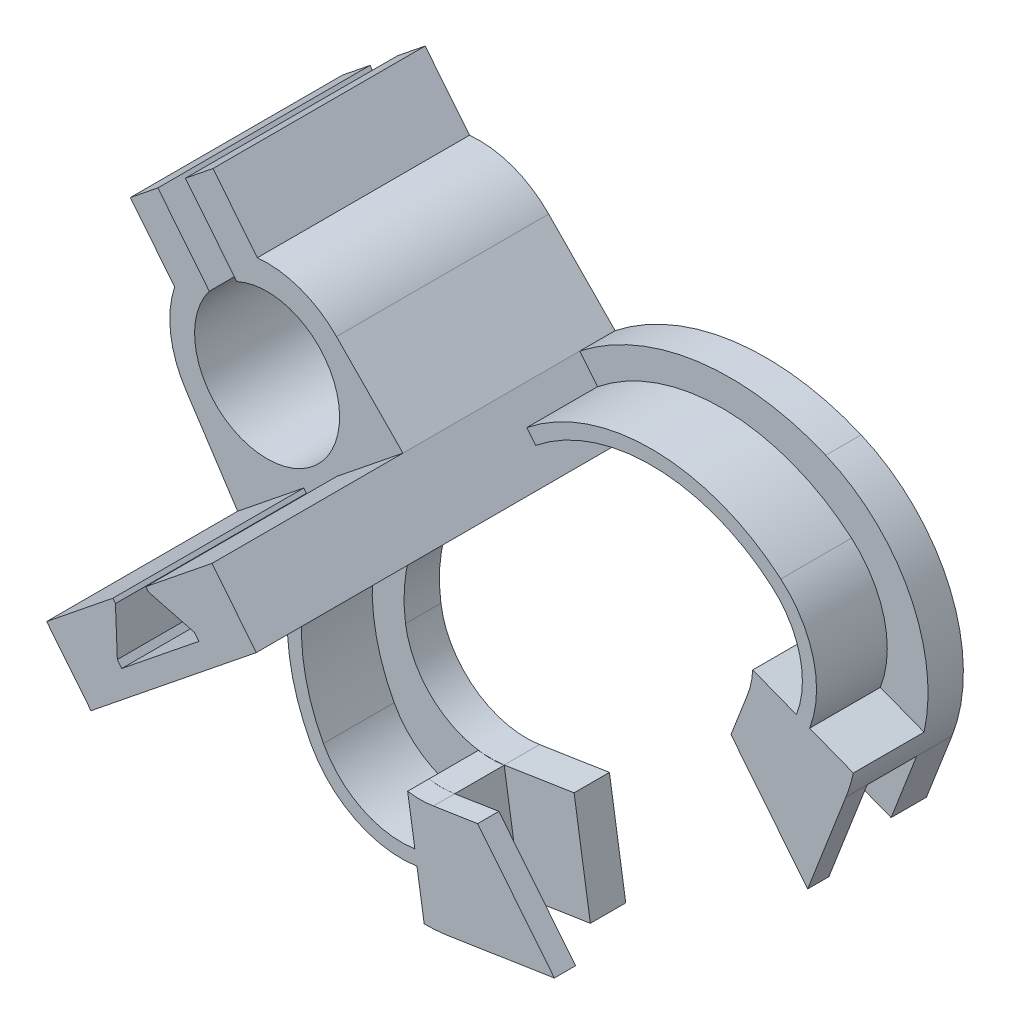
SolidWorks part; units mm, degrees
ref_plane "Piano frontale" through (0, 0, 0) normal (0, 0, 1) x (1, 0, 0)
ref_plane "Piano superiore" through (0, 0, 0) normal (0, 1, 0) x (1, 0, 0)
ref_plane "Piano destro" through (0, 0, 0) normal (1, 0, 0) x (0, 0, -1)
sketch "Schizzo1" plane through (0, 0, 0) normal (0, 0, 1) x (1, 0, 0)
  line L0 (-85.2957, -151.7534) -> (-82.9959, -166.5844) construction
  line L1 (-82.9959, -166.5844) -> (-92.8778, -168.1167)
  line L2 (-85.2957, -151.7534) -> (-95.1776, -153.2857)
  line L3 (-54.4678, -126.9553) -> (-50.8535, -117.6313)
  line L4 (-54.4678, -126.9553) -> (-40.4741, -132.3797)
  line L5 (-85.2957, -151.7534) -> (-82.9959, -166.5844)
  line L6 (-86.4258, -146.4666) -> (-55.0866, -185.4262) construction
  line L7 (-86.4258, -146.4666) -> (-82.5194, -151.3228) construction
  line L8 (-82.5194, -151.3228) -> (-85.2957, -151.7534) construction
  line L9 (-93.6828, -160.6477) -> (-84.1458, -159.1689) construction
  line L10 (-96.0578, -145.3317) -> (-91.3078, -175.9638) construction
  line L11 (-86.4258, -146.4666) -> (-59.3896, -124.7186) construction
  line L12 (-59.3896, -124.7186) -> (-28.0504, -163.6782) construction
  line L13 (-28.0504, -163.6782) -> (-55.0866, -185.4262) construction
  line L14 (-72.9077, -135.5926) -> (-41.5685, -174.5522) construction
  line L15 (-58.4342, -115.0671) -> (-29.5315, -126.2708) construction
  line L16 (-43.9828, -120.669) -> (-47.471, -129.6675) construction
  line L17 (-54.4678, -126.9553) -> (-40.4741, -132.3797) construction
  line L18 (-89.9122, -114.4533) -> (-96.18, -106.6614) construction
  line L19 (-101.6001, -123.8551) -> (-78.2243, -105.0516) construction
  line L20 (-40.4741, -132.3797) -> (-36.8598, -123.0557)
  line L21 (-101.6001, -123.8551) -> (-107.8679, -116.0632) construction
  line L22 (-107.8679, -116.0632) -> (-84.4922, -97.2597) construction
  line L23 (-78.2243, -105.0516) -> (-84.4922, -97.2597) construction
  line L24 (-107.8679, -116.0632) -> (-84.4922, -97.2597)
  line L25 (-101.6001, -123.8551) -> (-78.2243, -105.0516)
  arc A0 (-92.8778, -168.1167) -> (-109.249, -157.2329) centre (-95.4408, -154.2175) cw construction
  arc A1 (-95.1776, -153.2857) -> (-106.6488, -144.6211) centre (-97.8823, -144.9407) cw construction
  arc A2 (-50.8535, -117.6313) -> (-56.8589, -104.5699) centre (-58.4251, -113.2013) ccw construction
  arc A3 (-95.1776, -153.2857) -> (-109.1299, -142.9563) centre (-97.0479, -141.2244) cw
  arc A4 (-36.8598, -123.0557) -> (-43.9828, -104.7326) centre (-49.887, -117.5739) ccw construction
  arc A5 (-92.8778, -168.1167) -> (-119.8406, -149.0462) centre (-96.5147, -144.6629) cw
  arc A6 (-119.8406, -149.0462) -> (-107.8679, -116.0632) centre (-85.9613, -142.6797) cw
  arc A7 (-50.8535, -117.6313) -> (-57.9534, -101.7897) centre (-62.2339, -113.2199) ccw
  arc A8 (-57.9534, -101.7897) -> (-78.2243, -105.0516) centre (-65.2262, -121.2102) ccw
  arc A9 (-109.1299, -142.9563) -> (-101.6001, -123.8551) centre (-88.602, -140.0138) cw
  arc A10 (-36.8598, -123.0557) -> (-49.7097, -92.6327) centre (-58.9895, -114.4775) ccw
  arc A11 (-49.7097, -92.6327) -> (-84.4922, -97.2597) centre (-63.1881, -124.3609) ccw
  dimension "D3" = 30
  dimension "D1" = 10
  dimension "D2" = 10
  dimension "D4" = 15.0083
  dimension "D5" = 10
extrude "Estrusione-Estrusione1" add sketch "Schizzo1" along normal blind 5
sketch "Schizzo2" plane through (0, 0, 5) normal (0, 0, 1) x (1, 0, 0)
  line L1 (-36.8598, -123.0557) -> (-50.8308, -117.6401)
  line L2 (-54.4678, -126.9553) -> (-85.2957, -151.7534) construction
  line L3 (-96.4908, -168.397) -> (-98.8284, -153.3228)
  line L4 (-85.2957, -151.7534) -> (-69.8818, -139.3543) construction
  line L5 (-69.8818, -139.3543) -> (-58.455, -153.5596) construction
  line L6 (-35.8118, -119.5867) -> (-50.035, -114.0733)
  line L7 (-92.8778, -168.1167) -> (-95.1739, -153.3098)
  arc A1 (-95.1739, -153.3098) -> (-109.1299, -142.9563) centre (-97.0443, -141.2482) cw construction
  arc A2 (-36.8598, -123.0557) -> (-49.4205, -92.7579) centre (-58.9895, -114.4775) ccw construction
  arc A3 (-92.8778, -168.1167) -> (-119.7803, -149.3556) centre (-96.5147, -144.6629) cw construction
  arc A4 (-119.8406, -149.0462) -> (-92.8778, -168.1167) centre (-96.5147, -144.6629) ccw construction
  arc A5 (-95.1739, -153.3098) -> (-98.8284, -153.3228) centre (-97.0443, -141.2482) cw
  arc A6 (-92.8778, -168.1167) -> (-96.4908, -168.397) centre (-96.5147, -144.6629) cw
  arc A7 (-50.8308, -117.6401) -> (-57.9534, -101.7897) centre (-62.2115, -113.2286) ccw construction
  arc A8 (-36.8598, -123.0557) -> (-35.8118, -119.5867) centre (-58.9895, -114.4775) ccw
  arc A9 (-50.8308, -117.6401) -> (-50.035, -114.0733) centre (-62.2115, -113.2286) ccw
extrude "Estrusione-Estrusione2" add sketch "Schizzo2" along normal blind 7
sketch "Schizzo3" plane through (0, 0, 12) normal (0, 0, 1) x (1, 0, 0)
  line L0 (-42.2706, -137.0142) -> (-36.8598, -123.0557)
  line L1 (-92.8778, -168.1167) -> (-95.1739, -153.3098) construction
  line L2 (-96.4908, -168.397) -> (-98.8284, -153.3228)
  line L3 (-95.1739, -153.3098) -> (-88.9286, -152.3413)
  line L4 (-98.8284, -153.3228) -> (-50.035, -114.0733) construction
  line L5 (-88.9286, -152.3413) -> (-78.0841, -165.8227)
  line L6 (-78.0841, -165.8227) -> (-92.8778, -168.1167)
  line L7 (-74.4317, -133.6981) -> (-68.2857, -141.3384) construction
  line L8 (-53.115, -123.5328) -> (-42.2706, -137.0142)
  line L9 (-50.8308, -117.6401) -> (-53.115, -123.5328)
  line L10 (-35.8118, -119.5867) -> (-50.035, -114.0733)
  line L11 (-92.3385, -148.1024) -> (-73.9828, -170.9213) construction
  arc A0 (-50.8308, -117.6401) -> (-50.035, -114.0733) centre (-61.3918, -113.4115) ccw
  arc A1 (-92.8778, -168.1167) -> (-96.4908, -168.397) centre (-96.5147, -144.6629) cw
  arc A2 (-36.8598, -123.0557) -> (-35.8118, -119.5867) centre (-58.9895, -114.4775) ccw
  arc A3 (-95.1739, -153.3098) -> (-98.8284, -153.3228) centre (-97.0413, -142.088) cw
extrude "Estrusione-Estrusione3" add sketch "Schizzo3" along normal blind 3
sketch "Schizzo4" plane through (0, 0, 5) normal (0, 0, 1) x (1, 0, 0)
  line L0 (-98.1478, -153.7091) -> (-49.8036, -114.8208) construction
  line L2 (-73.9757, -134.2649) -> (-78.3251, -128.858) construction
  line L3 (-101.6001, -123.8551) -> (-78.2243, -105.0516)
  line L4 (-101.6001, -123.8551) -> (-107.8679, -116.0632)
  line L5 (-107.8679, -116.0632) -> (-84.4922, -97.2597)
  line L6 (-78.2243, -105.0516) -> (-84.4922, -97.2597)
  line L7 (-89.9122, -114.4533) -> (-96.18, -106.6614) construction
  dimension "D1" = 30
  dimension "D2" = 10
extrude "Estrusione-Estrusione4" add sketch "Schizzo4" along normal blind 52
sketch "Schizzo5" plane through (0, 0, 57) normal (0, 0, 1) x (1, 0, 0)
  line L0 (-97.2469, -116.5033) -> (-97.8737, -115.7241)
  line L1 (-100.8552, -110.4221) -> (-89.1673, -101.0204) construction
  line L2 (-84.4922, -97.2597) -> (-107.8679, -116.0632) construction
  line L3 (-107.8679, -116.0632) -> (-101.6001, -123.8551) construction
  line L4 (-101.6001, -123.8551) -> (-78.2243, -105.0516) construction
  line L8 (-98.5176, -108.5418) -> (-93.8425, -104.7811)
  line L9 (-98.5176, -108.5418) -> (-98.1416, -109.0093)
  line L10 (-93.8425, -104.7811) -> (-93.4664, -105.2486)
  line L13 (-86.3382, -107.7283) -> (-86.965, -106.9491)
  line L14 (-98.1416, -109.0093) -> (-97.8737, -115.7241)
  line L15 (-86.965, -106.9491) -> (-93.4664, -105.2486)
  line L16 (-86.3382, -107.7283) -> (-97.2469, -116.5033)
  dimension "D1" = 14
  dimension "D2" = 7
  dimension "D3" = 8
  dimension "D4" = 6
  dimension "D5" = 0.6
  dimension "D6" = 1
extrude "Taglio-Estrusione2" cut sketch "Schizzo5" against normal offset from surface (27 mm away) 30 up to face at (-78.2798, -128.9143, 0)
sketch "Schizzo6" plane through (0, 0, 5) normal (0, 0, 1) x (1, 0, 0)
  line L0 (-98.8284, -153.3228) -> (-96.5147, -168.3971) construction
  line L1 (-107.8679, -116.0632) -> (-101.6001, -123.8551) construction
  line L2 (-101.6001, -123.8551) -> (-78.2243, -105.0516) construction
  line L3 (-84.4922, -97.2597) -> (-78.2243, -105.0516) construction
  line L4 (-81.3582, -101.1556) -> (-104.734, -119.9592) construction
  line L5 (-97.6716, -160.8599) -> (-84.2642, -158.8022) construction
  line L6 (-97.8233, -159.8715) -> (-92.3417, -159.0302) construction
  line L7 (-92.3417, -159.0302) -> (-92.0383, -161.0071) construction
  line L8 (-92.0383, -161.0071) -> (-97.5198, -161.8484) construction
  line L9 (-89.9122, -114.4533) -> (-84.2642, -121.4746) construction
  line L10 (-43.9843, -122.3523) -> (-41.9879, -117.1783) construction
  line L11 (-45.8502, -121.6323) -> (-43.9843, -122.3523) construction
  line L12 (-43.8538, -116.4583) -> (-45.8502, -121.6323) construction
  line L13 (-42.9208, -116.8183) -> (-47.8038, -129.4733) construction
  line L14 (-50.035, -114.0733) -> (-35.8067, -119.5633) construction
  line L15 (-105.3608, -119.18) -> (-104.1072, -120.7383)
  line L16 (-97.5198, -161.8484) -> (-97.8233, -159.8715)
  line L17 (-43.8538, -116.4583) -> (-41.9879, -117.1783)
  line L18 (-81.985, -100.3764) -> (-80.7315, -101.9348)
  line L19 (-97.5198, -161.8484) -> (-97.5066, -161.8464)
  line L20 (-98.8284, -153.3228) -> (-96.4908, -168.397) construction
  line L21 (-97.5066, -161.8464) -> (-97.8131, -159.87)
  line L22 (-97.8131, -159.87) -> (-97.8233, -159.8715)
  line L23 (-41.9927, -117.1908) -> (-41.9879, -117.1783)
  line L24 (-35.8118, -119.5867) -> (-50.035, -114.0733) construction
  line L25 (-41.9927, -117.1908) -> (-43.8575, -116.4679)
  line L26 (-43.8575, -116.4679) -> (-43.8538, -116.4583)
  arc A1 (-97.6716, -160.8599) -> (-111.6123, -153.9104) centre (-99.7202, -147.5122) cw construction
  arc A2 (-111.6123, -153.9104) -> (-104.734, -119.9592) centre (-87.7506, -141.0723) cw construction
  arc A3 (-46.7217, -101.7122) -> (-81.3582, -101.1556) centre (-64.3748, -122.2687) ccw construction
  arc A4 (-42.9208, -116.8183) -> (-46.7217, -101.7122) centre (-55.5196, -111.9571) ccw construction
  arc A5 (-97.8233, -159.8715) -> (-110.7317, -153.4366) centre (-99.7202, -147.5122) cw
  arc A6 (-110.7317, -153.4366) -> (-104.1072, -120.7383) centre (-87.7506, -141.0723) cw
  arc A7 (-97.5198, -161.8484) -> (-112.493, -154.3842) centre (-99.7202, -147.5122) cw
  arc A8 (-112.493, -154.3842) -> (-105.3608, -119.18) centre (-87.7506, -141.0723) cw
  arc A9 (-46.0702, -100.9535) -> (-81.985, -100.3764) centre (-64.3748, -122.2687) ccw
  arc A10 (-41.9879, -117.1783) -> (-46.0702, -100.9535) centre (-55.5196, -111.9571) ccw
  arc A11 (-47.3732, -102.4708) -> (-80.7315, -101.9348) centre (-64.3748, -122.2687) ccw
  arc A12 (-43.8538, -116.4583) -> (-47.3732, -102.4708) centre (-55.5196, -111.9571) ccw
  point P10 (-97.6716, -160.8599)
  point P11 (-104.734, -119.9592)
  point P13 (-97.8233, -159.8715)
  point P16 (-81.3582, -101.1556)
  point P24 (-97.5198, -161.8484)
  point P30 (-104.1072, -120.7383)
  point P33 (-105.3608, -119.18)
  line M4 (-101.6001, -123.8551) -> (-107.8679, -116.0632)
  line M7 (-96.4908, -168.397) -> (-98.8284, -153.3228)
  dimension "D3" = 1
  dimension "D4" = 1
  dimension "D5" = 1
  dimension "D6" = 1
extrude "Estrusione-Estrusione8" add sketch "Schizzo6" along normal up to surface (10 mm away) contours L22 L16 L19 M7 | A8 A7 L16 A5 A6 M4 | A12 L17 A10 A9 L18 A11 | L26 L25 L23 L17 up to face at (-44.7854, -122.4925, 15)
sketch "Schizzo9" plane through (0, 0, 0) normal (0, 0, -1) x (-1, 0, 0)
  line L0 (84.4922, -97.2597) -> (107.8679, -116.0632) construction
  line L1 (96.18, -106.6614) -> (103.7015, -97.3111) construction
  line L2 (93.885, -87.683) -> (84.4922, -97.2597)
  line L3 (115.2094, -104.8364) -> (107.8679, -116.0632)
  line L4 (84.4922, -97.2597) -> (107.8679, -116.0632)
  line L5 (105.0809, -83.6305) -> (111.3487, -75.8386)
  line L6 (111.3487, -75.8386) -> (115.2447, -78.9725)
  line L7 (115.2447, -78.9725) -> (107.984, -87.9986)
  line L8 (111.88, -91.1326) -> (119.1406, -82.1064)
  line L9 (119.1406, -82.1064) -> (123.0366, -85.2403)
  line L10 (123.0366, -85.2403) -> (116.7687, -93.0322)
  circle A0 centre (103.7015, -97.3111) radius 10.25 construction
  circle A1 centre (103.7015, -97.3111) radius 13.75 construction
  arc A2 (107.984, -87.9986) -> (111.88, -91.1326) centre (103.7015, -97.3111) ccw
  arc A5 (93.885, -87.683) -> (105.0809, -83.6305) centre (103.7015, -97.3111) cw
  arc A6 (115.2094, -104.8364) -> (116.7687, -93.0322) centre (103.7015, -97.3111) ccw
  dimension "D1" = 20.5
  dimension "D3" = 3.5
  dimension "D2" = 12
  dimension "D4" = 5
  dimension "D5" = 5
  dimension "D6" = 2.5
  dimension "D7" = 10
extrude "Estrusione-Estrusione6" add sketch "Schizzo9" against normal blind 30
sketch "Schizzo10" plane through (18.6942, -23.2399, 0) normal (-0.6268, 0.7792, 0) x (0.7792, 0.6268, 0)
  line L0 (-148.7965, -57) -> (-134.7965, -57) construction
  line L1 (-134.7965, -30) -> (-148.7965, -30)
  line L2 (-134.7965, -30) -> (-134.7965, -37)
  line L3 (-134.7965, -37) -> (-148.7965, -37)
  line L4 (-148.7965, -30) -> (-148.7965, -37)
  line L5 (-148.7965, -30) -> (-148.7965, -57) construction
  line L6 (-134.7965, -30) -> (-134.7965, -57) construction
  dimension "D1" = 27
  dimension "D2" = 20
extrude "Estrusione-Estrusione7" add sketch "Schizzo10" along normal blind 0.3
